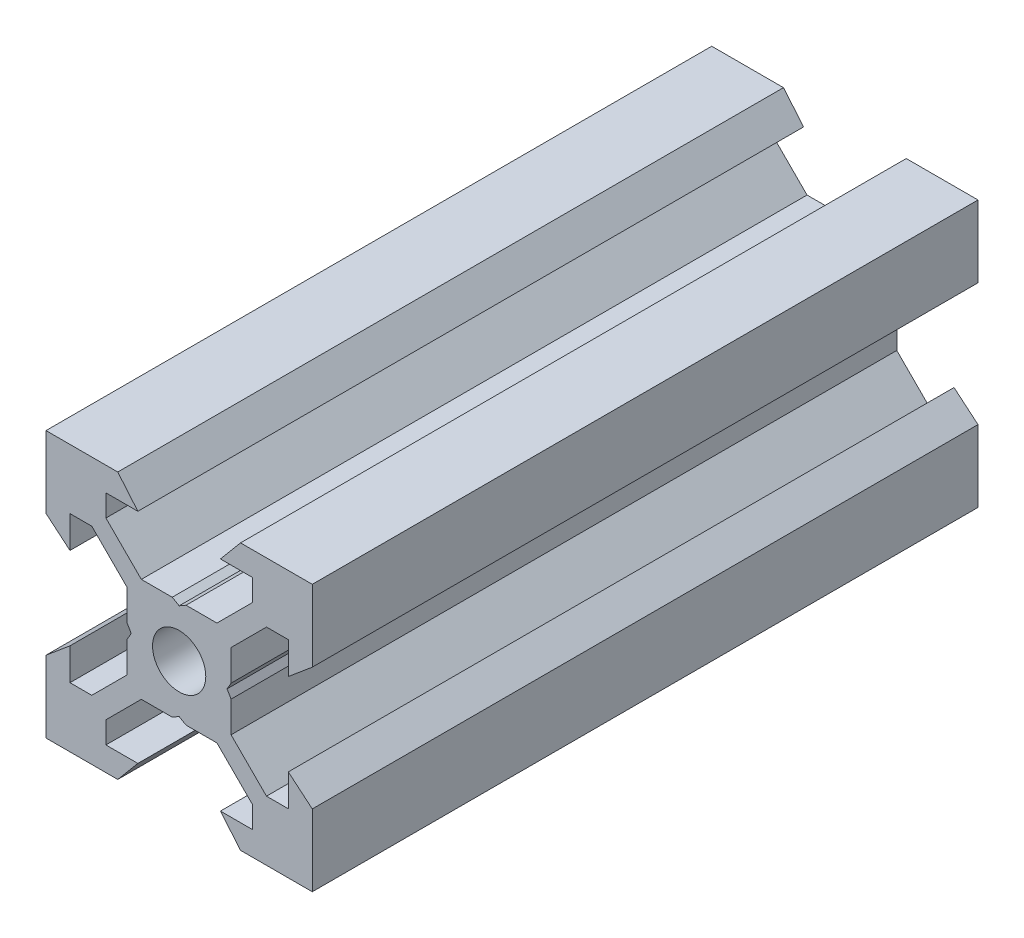
SolidWorks part; units mm, degrees
ref_plane "Front Plane" through (0, 0, 0) normal (0, 0, 1) x (1, 0, 0)
ref_plane "Top Plane" through (0, 0, 0) normal (0, 1, 0) x (1, 0, 0)
ref_plane "Right Plane" through (0, 0, 0) normal (1, 0, 0) x (0, 0, -1)
sketch "Sketch1" plane through (0, 0, 0) normal (0, 0, 1) x (1, 0, 0)
  line L0 (10, 10) -> (4.6104, 10) construction
  line L1 (10, 10) -> (10, 4.6104) construction
  line L2 (10, -10) -> (10, -4.6104) construction
  line L3 (10, -10) -> (4.6104, -10) construction
  line L4 (10, 10) -> (10, 4.6104)
  line L5 (6.5607, 5.5) -> (8.2, 5.5)
  line L6 (5.5, 8.2) -> (5.5, 6.5607)
  line L7 (10, 10) -> (4.6104, 10)
  line L8 (10, 10) -> (10, 4.6104)
  line L9 (6.5607, 5.5) -> (3.9, 2.8393)
  line L10 (5.5, 6.5607) -> (2.8393, 3.9)
  line L11 (10, 4.6104) -> (8.2, 3.1)
  line L12 (4.6104, 10) -> (3.1, 8.2)
  line L13 (8.2, 3.1) -> (8.2, 5.5)
  line L14 (3.1, 8.2) -> (5.5, 8.2)
  line L15 (-6.5607, 5.5) -> (-8.2, 5.5)
  line L16 (6.5607, -5.5) -> (8.2, -5.5)
  line L17 (3.1, -8.2) -> (5.5, -8.2)
  line L18 (8.2, -3.1) -> (8.2, -5.5)
  line L19 (4.6104, -10) -> (3.1, -8.2)
  line L20 (10, -4.6104) -> (8.2, -3.1)
  line L21 (0.5196, -3.9) -> (0, -3.6)
  line L22 (0.5196, 3.9) -> (0, 3.6)
  line L23 (3.6, 0) -> (3.9, -0.5196)
  line L24 (3.9, 0.5196) -> (3.6, 0)
  line L25 (3.9, 0.5196) -> (3.9, 2.8393)
  line L26 (2.8393, 3.9) -> (0.5196, 3.9)
  line L27 (3.9, -2.8393) -> (3.9, -0.5196)
  line L28 (2.8393, -3.9) -> (0.5196, -3.9)
  line L29 (5.5, -6.5607) -> (2.8393, -3.9)
  line L30 (6.5607, -5.5) -> (3.9, -2.8393)
  line L31 (10, -10) -> (10, -4.6104)
  line L32 (10, -10) -> (4.6104, -10)
  line L33 (5.5, -8.2) -> (5.5, -6.5607)
  line L34 (-6.5607, -5.5) -> (-8.2, -5.5)
  line L35 (10, -10) -> (10, -4.6104)
  line L36 (0, 0) -> (0, 8.2) construction
  line L37 (-10, -10) -> (-4.6104, -10) construction
  line L38 (-10, -10) -> (-10, -4.6104) construction
  line L39 (-10, 10) -> (-10, 4.6104) construction
  line L40 (-10, 10) -> (-4.6104, 10) construction
  line L41 (-10, -10) -> (-10, -4.6104)
  line L43 (-5.5, -8.2) -> (-5.5, -6.5607)
  line L44 (-10, -10) -> (-4.6104, -10)
  line L45 (-10, -10) -> (-10, -4.6104)
  line L46 (-6.5607, -5.5) -> (-3.9, -2.8393)
  line L47 (-5.5, -6.5607) -> (-2.8393, -3.9)
  line L48 (-2.8393, -3.9) -> (-0.5196, -3.9)
  line L49 (-3.9, -2.8393) -> (-3.9, -0.5196)
  line L50 (-2.8393, 3.9) -> (-0.5196, 3.9)
  line L51 (-3.9, 0.5196) -> (-3.9, 2.8393)
  line L52 (-3.9, 0.5196) -> (-3.6, 0)
  line L53 (-3.6, 0) -> (-3.9, -0.5196)
  line L54 (-0.5196, 3.9) -> (0, 3.6)
  line L55 (-0.5196, -3.9) -> (0, -3.6)
  line L56 (-10, -4.6104) -> (-8.2, -3.1)
  line L57 (-4.6104, -10) -> (-3.1, -8.2)
  line L58 (-8.2, -3.1) -> (-8.2, -5.5)
  line L59 (-3.1, -8.2) -> (-5.5, -8.2)
  line L60 (-10, -10) -> (10, -10) construction
  line L61 (-10, -10) -> (-10, 10) construction
  line L62 (-3.1, 8.2) -> (-5.5, 8.2)
  line L63 (-8.2, 3.1) -> (-8.2, 5.5)
  line L64 (-4.6104, 10) -> (-3.1, 8.2)
  line L65 (-10, 4.6104) -> (-8.2, 3.1)
  line L66 (-5.5, 6.5607) -> (-2.8393, 3.9)
  line L67 (-6.5607, 5.5) -> (-3.9, 2.8393)
  line L68 (-10, 10) -> (-10, 4.6104)
  line L69 (-10, 10) -> (-4.6104, 10)
  line L70 (-5.5, 8.2) -> (-5.5, 6.5607)
  line L71 (-10, 10) -> (10, 10) construction
  line L72 (-10, 10) -> (-10, 4.6104)
  line L73 (10, -10) -> (10, 10) construction
  line L74 (-10, -10) -> (10, 10) construction
  line L75 (-10, 10) -> (10, -10) construction
  circle A0 centre (0, 0) radius 2
  dimension "D7" = 4
  dimension "D1" = 20
  dimension "D2" = 5.3896
  dimension "D3" = 4.5
  dimension "D4" = 50
  dimension "D5" = 1.8
  dimension "D6" = 1.5104
  dimension "D8" = 5.5
  dimension "D9" = 120
  dimension "D10" = 0.3
  dimension "D11" = 2.3197
  dimension "D12" = 7.8
  dimension "D13" = 7.8
  dimension "D14" = 1.5
  dimension "D15" = 2.6607
extrude "Boss-Extrude1" add sketch "Sketch1" along normal mid plane 50 contours L70 L62 L64 L69 L68 L65 L63 L15 L67 L51 L52 L53 L49 L46 L34 L58 L56 L41 L44 L57 L59 L43 L47 L48 L55 L21 L28 L29 L33 L17 L19 L32 L31 L20 L18 L16 L30 L27 L23 L24 L25 L9 L5 L13 L11 L4 L7 L12 L14 L6 L10
